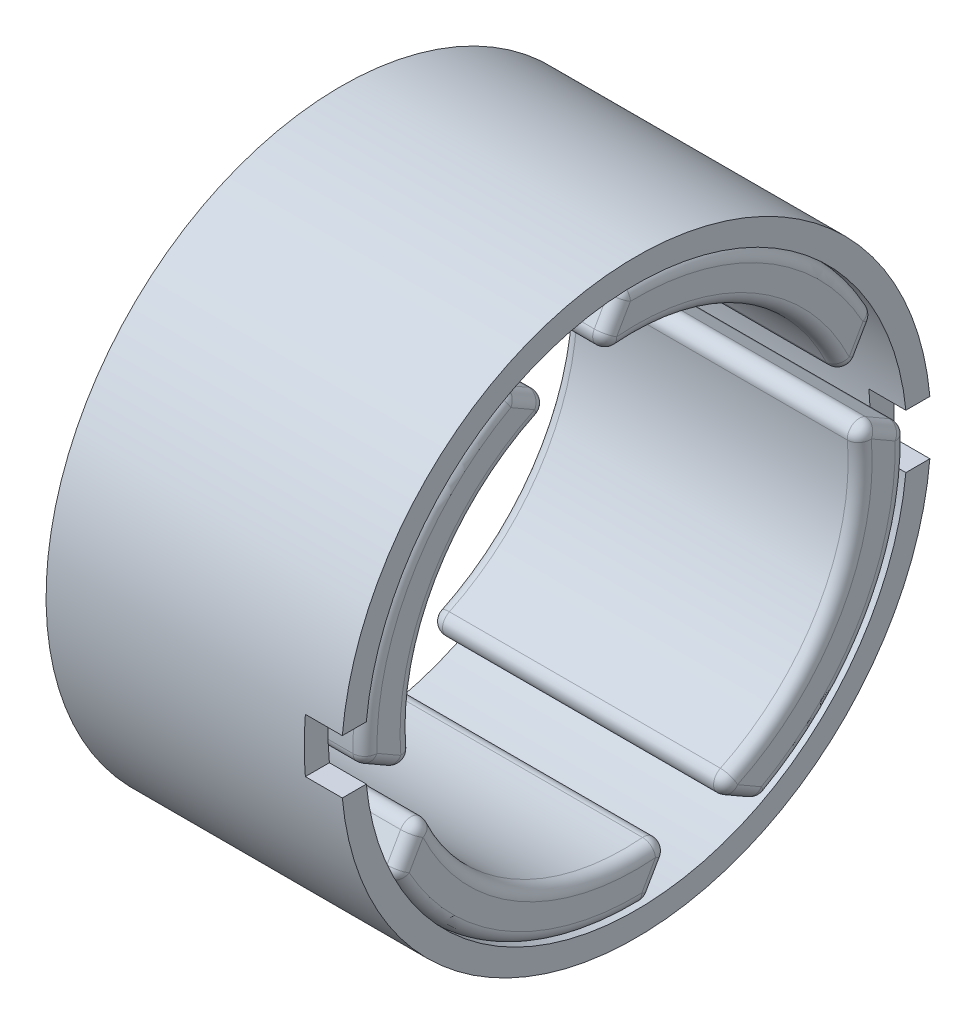
SolidWorks part; units mm, degrees
material "Galvanized Steel"
ref_plane "Front Plane" through (0, 0, 0) normal (0, 0, 1) x (1, 0, 0)
ref_plane "Top Plane" through (0, 0, 0) normal (0, 1, 0) x (1, 0, 0)
ref_plane "Right Plane" through (0, 0, 0) normal (1, 0, 0) x (0, 0, -1)
sketch "Sketch2" plane through (0, 0, 0) normal (1, 0, 0) x (0, 0, -1)
  circle A0 centre (0, 0) radius 25
  circle A1 centre (0, 0) radius 22.9743
  dimension "D1" = 50
  dimension "D2" = 45.9486
extrude "Boss-Extrude1" add sketch "Sketch2" along normal blind 25
sketch "Sketch3" plane through (0, 0, 0) normal (0, 0, 1) x (1, 0, 0)
  line L0 (0, 0) -> (23.4347, 0) construction
  line L1 (25, -2.286) -> (21.8694, -2.286)
  line L2 (25, -2.286) -> (25, 2.286)
  line L3 (25, 2.286) -> (21.8694, 2.286)
  line L4 (21.8694, -2.286) -> (21.8694, 2.286)
  line L5 (25, -2.286) -> (21.8694, 2.286) construction
  line L6 (25, 2.286) -> (21.8694, -2.286) construction
  line L7 (0, 25) -> (0, -25) construction
  line L8 (25, -25) -> (25, 25) construction
  point P0 (23.4347, 0)
  dimension "D1" = 21.8694
  dimension "D2" = 4.572
extrude "Cut-Extrude1" cut sketch "Sketch3" against normal through all and the other way through all
sketch "Sketch4" plane through (0, 0, 0) normal (1, 0, 0) x (0, 0, -1)
  line L0 (-22.9487, -1.0833) -> (-18.6505, -3.556)
  line L2 (-6.3014, 17.9103) -> (-10.5996, 20.383)
  line L3 (-19.9142, 11.4562) -> (0, 0) construction
  line L4 (-27.0848, -3.556) -> (-14.2951, -3.556) construction
  line L5 (-22.8603, -2.286) -> (-24.8953, -2.286) construction
  arc A0 (-22.9487, -1.0833) -> (-10.5996, 20.383) centre (0, 0) cw
  arc A1 (22.8603, 2.286) -> (-22.8603, 2.286) centre (0, 0) ccw construction
  arc A2 (-18.6505, -3.556) -> (-6.3014, 17.9103) centre (0, 0) cw
  dimension "D1" = 18.9865
  dimension "D2" = 1.27
  dimension "D3" = 24.765
extrude "Boss-Extrude2" add sketch "Sketch4" along normal up to surface (25 mm away) separate body up to face at (25, 13.1366, 0)
fillet "Fillet1" radius 1.016 12 edges at (12.5, -1.0833, 22.9487) (0, -2.3197, 20.7996) (0, 11.4562, 19.9142) (12.5, 20.383, 10.5996) (0, 19.1467, 8.4505) (25, -2.3197, 20.7996) (25, 11.4562, 19.9142) (25, 19.1467, 8.4505) (12.5, 17.9103, 6.3014) (0, 9.4677, 16.4575) (12.5, -3.556, 18.6505) (25, 9.4677, 16.4575)
pattern_circular "CirPattern1" count 4 over 360 about axis through (0, 0, 0) along (1, 0, 0) of bodies 103
ref_plane "Midmagnet plane" through (12.5, 0, 0) normal (1, 0, 0) x (0, 0, -1)
